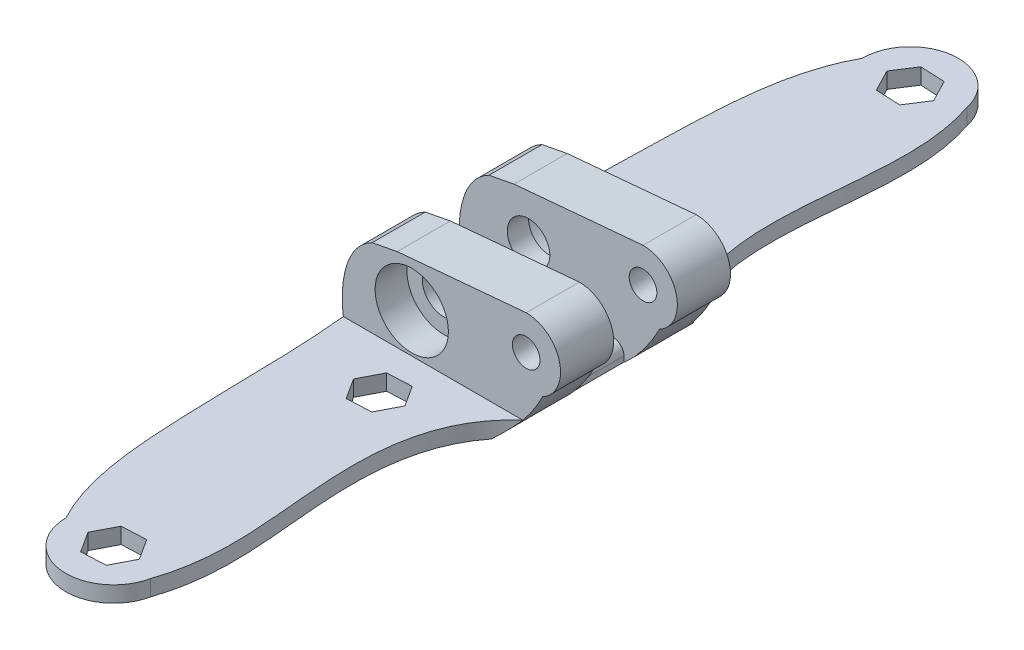
SolidWorks part; units mm, degrees
ref_plane "Front Plane" through (0, 0, 0) normal (0, 0, 1) x (1, 0, 0)
ref_plane "Top Plane" through (0, 0, 0) normal (0, 1, 0) x (1, 0, 0)
ref_plane "Right Plane" through (0, 0, 0) normal (1, 0, 0) x (0, 0, -1)
sketch "Sketch1" plane through (0, 0, 0) normal (0, 0, 1) x (1, 0, 0)
  line L0 (-139.182, -34.0354) -> (-124.7357, -34.0354)
  line L5 (-155.0708, -34.0354) -> (-139.182, -34.0354)
  line L6 (-121.2243, -13.1941) -> (-145.5043, -15.3702)
  arc A0 (-118.1107, -25.3371) -> (-122.3749, -13.2972) centre (-121.2243, -19.6648) ccw
  circle A1 centre (-121.2243, -19.6648) radius 2.6
  circle A2 centre (-142.7777, -23.6192) radius 6.9
  spline S0 degree 2 poles (-124.7357, -34.0354) (-120.8681, -30.6349) (-118.1107, -25.3371) knots 0.604914 0.604914 0.604914 1 1 1
  spline S1 degree 2 poles (-145.5043, -15.3702) (-147.6654, -15.752) (-150.2379, -16.2788) knots 0 0 0 0.143499 0.143499 0.143499
  spline S2 degree 3 poles (-150.2379, -16.2788) (-156.3314, -19.4124) (-156.5873, -28.5049) (-155.0708, -34.0354) knots 0 0 0 0 1 1 1 1
extrude "Boss-Extrude1" add sketch "Sketch1" along normal blind 10
sketch "Sketch2" plane through (0, 0, 0) normal (0, 0, -1) x (-1, 0, 0)
  line L1 (155.0708, -34.0354) -> (124.7357, -34.0354) construction
  line L2 (124.8108, -34.0354) -> (124.8108, -33.0354)
  line L3 (126.8108, -31.0354) -> (155.6602, -31.0354)
  line L4 (124.8108, -34.0354) -> (155.0708, -34.0354)
  arc A0 (124.8108, -33.0354) -> (126.8108, -31.0354) centre (126.8108, -33.0354) cw
  spline S1 degree 2 poles (155.6602, -31.0354) (155.4533, -32.2208) (155.0708, -34.0354) knots 0.46928 0.46928 0.46928 1.113861 1.113861 1.113861
  spline S2 degree 3 poles (150.2379, -16.2788) (156.3314, -19.4124) (156.5873, -28.5049) (155.0708, -34.0354) knots 0 0 0 0 1 1 1 1 construction
  dimension "D2" = 2
  dimension "D1" = 3
extrude "Boss-Extrude2" add sketch "Sketch2" along normal blind 12
ref_plane "Plane1" through (0, 0, -6) normal (0, 0, -1) x (-1, 0, 0)
mirror "Mirror1" about plane through (0, 0, -6) normal (0, 0, -1) of "Boss-Extrude1"
sketch "Sketch3" plane through (0, 0, 0) normal (0, 0, -1) x (-1, 0, 0)
  circle A0 centre (142.7777, -23.6192) radius 4
  circle A1 centre (142.7777, -23.6192) radius 7
  dimension "D1" = 8
  dimension "D2" = 14
extrude "Boss-Extrude3" add sketch "Sketch3" against normal blind 4
mirror "Mirror2" about plane through (0, 0, -6) normal (0, 0, -1) of "Boss-Extrude3"
sketch "Sketch4" plane through (0, 0, 10) normal (0, 0, 1) x (1, 0, 0)
  line L3 (-155.0708, -34.0354) -> (-124.7357, -34.0354) construction
  line L4 (-155.0708, -34.0354) -> (-124.7357, -34.0354)
  line L5 (-155.6602, -31.0354) -> (-121.839, -31.0354)
  parabola Q0 (-124.7357, -34.0354) -> (-118.1107, -25.3371) focus (-134.2829, -26.659) apex (-128.4106, -36.6937) construction
  parabola Q1 (-124.7357, -34.0354) -> (-121.839, -31.0354) focus (-134.2829, -26.659) apex (-128.4106, -36.6937)
  spline S3 degree 3 poles (1418.4323, -2568.4115) (-1494.8779, 2800.3488) (936.9377, -2971.3238) (-991.0388, 2845.1787) knots -5.924969 -5.924969 -5.924969 -5.924969 7.440007 7.440007 7.440007 7.440007 only from (-150.2379, -16.2788) to (-155.0708, -34.0354) construction
  spline S4 degree 3 poles (-155.6602, -31.0354) (-155.5248, -32.1044) (-155.3221, -33.1188) (-155.0708, -34.0354) knots 0.834264 0.834264 0.834264 0.834264 1 1 1 1
  line M7 (-155.0708, -34.0354) -> (-124.7357, -34.0354)
  spline M9 degree 2 poles (-124.7357, -34.0354) (-120.8681, -30.6349) (-118.1107, -25.3371) knots 0.604914 0.604914 0.604914 1 1 1
  spline M15 degree 3 poles (-150.2379, -16.2788) (-156.3314, -19.4124) (-156.5873, -28.5049) (-155.0708, -34.0354) knots 0 0 0 0 1 1 1 1
  dimension "D1" = 3
extrude "Boss-Extrude4" add sketch "Sketch4" along normal blind 84 contours L5 M15 M7 M9
sketch "Sketch5" plane through (0, 0, -22) normal (0, 0, -1) x (-1, 0, 0)
  line L4 (155.0708, -34.0354) -> (124.7357, -34.0354) construction
  line L12 (155.6602, -31.0354) -> (121.839, -31.0354) construction
  line L13 (155.0708, -34.0354) -> (124.7357, -34.0354)
  line L14 (155.6602, -31.0354) -> (121.839, -31.0354)
  parabola Q1 (124.7357, -34.0354) -> (121.839, -31.0354) focus (134.2829, -26.659) apex (128.4106, -36.6937) construction
  parabola Q2 (124.7357, -34.0354) -> (121.839, -31.0354) focus (134.2829, -26.659) apex (128.4106, -36.6937)
  spline S0 degree 3 poles (-940.0385, -1700.278) (1070.9853, 1882.8118) (-569.2522, -2026.0721) (681.2923, 1894.3267) knots -5.104421 -5.104421 -5.104421 -5.104421 6.614169 6.614169 6.614169 6.614169 only from (155.6602, -31.0354) to (155.0708, -34.0354) construction
  spline S1 degree 3 poles (155.6602, -31.0354) (155.5248, -32.1044) (155.3221, -33.1188) (155.0708, -34.0354) knots 0.834264 0.834264 0.834264 0.834264 1 1 1 1
extrude "Boss-Extrude5" add sketch "Sketch5" along normal blind 84
ref_plane "Plane2" through (0, 0, -6) normal (0, 0, 1) x (1, 0, 0)
sketch "Sketch6" plane through (0, -31.0354, 0) normal (0, 1, 0) x (1, 0, 0)
  line L0 (-137.7864, 76.8948) -> (-142.4, 77.1142)
  line L1 (-142.4, 77.1142) -> (-144.5168, 81.2194)
  line L2 (-144.5168, 81.2194) -> (-142.0201, 85.1052)
  line L3 (-142.0201, 85.1052) -> (-137.4065, 84.8858)
  line L4 (-137.4065, 84.8858) -> (-135.2897, 80.7806)
  line L5 (-135.2897, 80.7806) -> (-137.7864, 76.8948)
  line L6 (-135.2897, 30.7806) -> (-137.7864, 26.8948)
  line L7 (-144.5168, 31.2194) -> (-142.0201, 35.1052)
  line L8 (-137.7864, 26.8948) -> (-142.4, 27.1142)
  line L9 (-137.4065, 34.8858) -> (-135.2897, 30.7806)
  line L10 (-142.4, 27.1142) -> (-144.5168, 31.2194)
  line L11 (-142.0201, 35.1052) -> (-137.4065, 34.8858)
  line L24 (-155.6602, 22) -> (-173.4653, 22)
  line L25 (-173.4653, 22) -> (-173.4653, 117.8341)
  line L26 (-173.4653, 117.8341) -> (-100.4309, 117.8341)
  line L27 (-100.4309, 117.8341) -> (-121.839, 22)
  line L28 (-252.8971, 6) -> (-193.8751, 6) construction
  line L29 (-100.4309, -105.8341) -> (-121.839, -10)
  line L30 (-173.4653, -105.8341) -> (-100.4309, -105.8341)
  line L31 (-173.4653, -10) -> (-173.4653, -105.8341)
  line L32 (-155.6602, -10) -> (-173.4653, -10)
  line L33 (-142.0201, -23.1052) -> (-137.4065, -22.8858)
  line L34 (-142.4, -15.1142) -> (-144.5168, -19.2194)
  line L35 (-137.4065, -22.8858) -> (-135.2897, -18.7806)
  line L36 (-137.7864, -14.8948) -> (-142.4, -15.1142)
  line L37 (-144.5168, -19.2194) -> (-142.0201, -23.1052)
  line L38 (-135.2897, -18.7806) -> (-137.7864, -14.8948)
  line L39 (-135.2897, -68.7806) -> (-137.7864, -64.8948)
  line L40 (-137.4065, -72.8858) -> (-135.2897, -68.7806)
  line L41 (-142.0201, -73.1052) -> (-137.4065, -72.8858)
  line L42 (-144.5168, -69.2194) -> (-142.0201, -73.1052)
  line L43 (-142.4, -65.1142) -> (-144.5168, -69.2194)
  line L44 (-137.7864, -64.8948) -> (-142.4, -65.1142)
  arc A0 (-131.072, 82.8635) -> (-148.929, 81) centre (-139.9032, 81) ccw
  arc A1 (-131.072, -70.8635) -> (-148.929, -69) centre (-139.9032, -69) cw
  spline S0 degree 3 poles (-121.839, 22) (-130.238, 29.2882) (-131.7087, 51.8195) (-127.4759, 72.231) (-131.072, 82.8635) knots 0 0 0 0 0.490729 1 1 1 1
  spline S1 degree 3 poles (-148.929, 81) (-152.6254, 74.0818) (-155.2624, 54.1051) (-154.4029, 34.2446) (-155.6602, 22) knots 0 0 0 0 0.385425 1 1 1 1
  spline S2 degree 3 poles (-148.929, -69) (-152.6254, -62.0818) (-155.2624, -42.1051) (-154.4029, -22.2446) (-155.6602, -10) knots 0 0 0 0 0.385425 1 1 1 1
  spline S3 degree 3 poles (-121.839, -10) (-130.238, -17.2882) (-131.7087, -39.8195) (-127.4759, -60.231) (-131.072, -70.8635) knots 0 0 0 0 0.490729 1 1 1 1
  point P14 (-252.8971, 6)
  point P15 (-193.8751, 6)
extrude "Cut-Extrude1" cut sketch "Sketch6" against normal through all
scale "Scale1" scale about centroid uniform scaling yes scale factor 1.5
